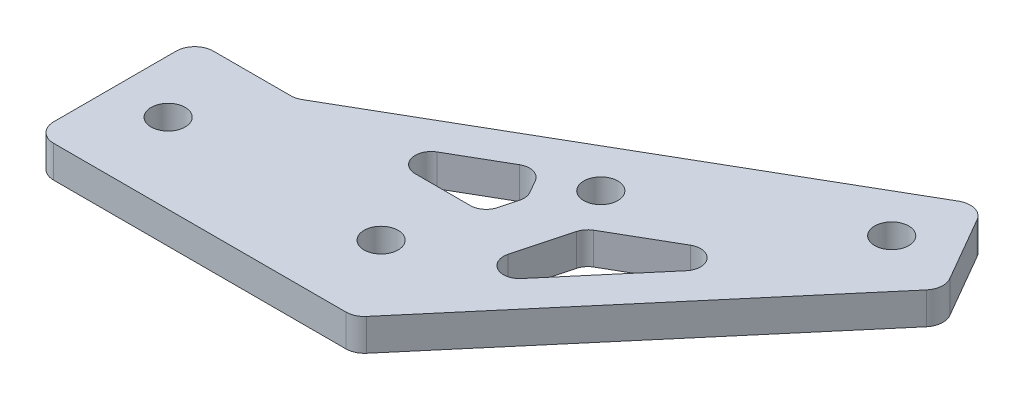
SolidWorks part; units mm, degrees
ref_plane "正面" through (0, 0, 0) normal (0, 0, 1) x (1, 0, 0)
ref_plane "平面" through (0, 0, 0) normal (0, 1, 0) x (1, 0, 0)
ref_plane "右側面" through (0, 0, 0) normal (1, 0, 0) x (0, 0, -1)
sketch "ｽｹｯﾁ1" plane through (0, 0, 0) normal (0, 1, 0) x (1, 0, 0)
  line L0 (164.476, -13.1178) -> (164.476, 1.8822) construction
  line L1 (164.476, 1.8822) -> (-55.524, 1.8822) construction
  line L3 (-55.524, -13.1178) -> (164.476, -13.1178) construction
  line L4 (26.6854, 10.5425) -> (31.6854, 1.8822) construction
  line L5 (31.6854, 1.8822) -> (334.7943, 176.8822) construction
  line L6 (334.7943, 176.8822) -> (329.7943, 185.5425) construction
  line L7 (329.7943, 185.5425) -> (26.6854, 10.5425) construction
  line L8 (164.476, -13.1178) -> (164.476, 1.8822) construction
  line L9 (164.476, 1.8822) -> (-55.524, 1.8822) construction
  line L11 (-55.524, -13.1178) -> (164.476, -13.1178) construction
  line L12 (26.6854, 10.5425) -> (31.6854, 1.8822) construction
  line L13 (31.6854, 1.8822) -> (334.7943, 176.8822) construction
  line L14 (334.7943, 176.8822) -> (329.7943, 185.5425) construction
  line L15 (329.7943, 185.5425) -> (26.6854, 10.5425) construction
  line L16 (29.47, 0) -> (419.1814, 225) construction
  line L17 (0, 0) -> (220, 0) construction
  line L18 (0, 0) -> (0, -15) construction
  line L19 (0, -15) -> (220, -15) construction
  line L20 (220, 0) -> (220, -15) construction
  line L21 (419.1814, 225) -> (414.1814, 233.6603) construction
  line L22 (414.1814, 233.6603) -> (24.47, 8.6603) construction
  line L23 (24.47, 8.6603) -> (29.47, 0) construction
  dimension "D1" = 15
  dimension "D2" = 220
  dimension "D3" = 29.47
  dimension "D4" = 30
  dimension "D5" = 450
  dimension "D6" = 10
sketch "ｽｹｯﾁ2" plane through (0, 0, 0) normal (0, 1, 0) x (1, 0, 0)
  line L0 (29.47, 0) -> (419.1814, 225) construction
  line L1 (24.47, 8.6603) -> (29.47, 0) construction
  line L2 (414.1814, 233.6603) -> (24.47, 8.6603) construction
  line L3 (220, 0) -> (220, -15) construction
  line L4 (0, -15) -> (220, -15) construction
  line L6 (0, 0) -> (220, 0) construction
  line L7 (29.47, 0) -> (419.1814, 225) construction
  line L8 (24.47, 8.6603) -> (29.47, 0) construction
  line L9 (414.1814, 233.6603) -> (24.47, 8.6603) construction
  line L10 (220, 0) -> (220, -15) construction
  line L11 (0, -15) -> (220, -15) construction
  line L13 (0, 0) -> (220, 0) construction
  line L14 (26.97, 4.3301) -> (48.6206, 16.8301) construction
  line L15 (0, -7.5) -> (25, -7.5) construction
  line L16 (24.47, 8.6603) -> (9.47, 0)
  line L18 (24.47, 8.6603) -> (50.4508, 23.6603)
  line L19 (50.4508, 23.6603) -> (55.4508, 15)
  line L20 (55.4508, 15) -> (30, -15)
  line L21 (30, -15) -> (0, -15)
  line L22 (0, -15) -> (0, 0)
  line L23 (0, 0) -> (9.47, 0)
  circle A0 centre (48.6206, 16.8301) radius 1.6
  circle A1 centre (25, -7.5) radius 1.6
  circle A2 centre (31.3001, 6.8301) radius 1.6
  circle A3 centre (5, -7.5) radius 1.6
  point P24 (0, -7.5)
  dimension "D3" = 3.2
  dimension "D4" = 3.2
  dimension "D5" = 3.2
  dimension "D6" = 3.2
  dimension "D1" = 25
  dimension "D2" = 25
  dimension "D7" = 5
  dimension "D8" = 5
  dimension "D9" = 5
  dimension "D10" = 5
extrude "ﾎﾞｽ - 押し出し1" add sketch "ｽｹｯﾁ2" along normal mid plane 3
sketch "ｽｹｯﾁ3" plane through (0, 1.5, 0) normal (0, 1, 0) x (1, 0, 0)
  line L0 (0, -15) -> (220, -15) construction
  line L1 (0, 0) -> (220, 0) construction
  line L2 (414.1814, 233.6603) -> (24.47, 8.6603) construction
  line L3 (24.47, 8.6603) -> (29.47, 0) construction
  line L4 (29.47, 0) -> (419.1814, 225) construction
  line L5 (0, -15) -> (220, -15)
  line L6 (0, 0) -> (220, 0)
  line L7 (414.1814, 233.6603) -> (24.47, 8.6603)
  line L8 (24.47, 8.6603) -> (29.47, 0)
  line L9 (29.47, 0) -> (419.1814, 225)
  line L10 (48.9867, 18.1962) -> (12.3252, -2.9704)
  line L11 (12.3252, -2.9704) -> (7.2558, -11)
  line L12 (7.2558, -11) -> (28.1479, -11)
  line L13 (28.1479, -11) -> (50.5782, 15.4396)
  line L14 (50.5782, 15.4396) -> (48.9867, 18.1962)
  line L15 (50.4508, 23.6603) -> (9.47, 0)
  line L16 (9.47, 0) -> (0, 0)
  line L17 (0, -15) -> (30, -15)
  line L18 (30, -15) -> (55.4508, 15)
  line L19 (55.4508, 15) -> (50.4508, 23.6603)
  line L20 (50.4508, 23.6603) -> (9.47, 0)
  line L22 (0, -15) -> (30, -15)
  line L23 (30, -15) -> (55.4508, 15)
  line L24 (55.4508, 15) -> (50.4508, 23.6603)
  line L25 (27.879, 2.7557) -> (27.1406, 0)
  line L26 (34.0628, 2.6517) -> (33.3523, 0)
  line L27 (0, -10.2338) -> (25, -7.5) construction
  line L28 (52.9508, 19.3301) -> (31.3001, 6.8301) construction
  line L29 (15.8097, 3.6603) -> (40.2703, -2.8939) construction
  line L30 (34.0628, 2.6517) -> (31.4468, -7.1115)
  line L37 (9.47, 0) -> (0, -15) construction
  line L38 (9.47, 0) -> (0, 0)
  line L39 (0, 0) -> (0, -15)
  line L40 (0, 0) -> (0, -15)
  dimension "D3" = 15
  dimension "D4" = 6
  dimension "D5" = 3.75
  dimension "D1" = 0
  dimension "D2" = 4
extrude "ｶｯﾄ - 押し出し1" cut sketch "ｽｹｯﾁ3" against normal blind 3 contours L25 L8 L10 L6 | L9 L26 L6 L13 | L6 L30 L13
fillet "ﾌｨﾚｯﾄ1" radius 1 7 edges at (45.1695, 0, -9.0641) (17.47, 0, 0) (26.47, 0, -5.1962) (27.879, 0, -2.7557) (27.1406, 0, 0) (31.4468, 0, 7.1115) (34.0628, 0, -2.6517)
fillet "ﾌｨﾚｯﾄ2" radius 1.75 6 edges at (50.4508, 0, -23.6603) (55.4508, 0, -15) (30, 0, 15) (9.47, 0, 0) (0, 0, 0) (0, 0, 15)
sketch "ｽｹｯﾁ4" plane through (0, -1.5, 0) normal (0, -1, 0) x (1, 0, 0)
  line L0 (50.4508, -23.6603) -> (55.4508, -15) construction
  line L1 (24.47, -8.6603) -> (50.4508, -23.6603) construction
  line L2 (24.47, -8.6603) -> (29.47, 0) construction
  line L3 (29.47, 0) -> (419.1814, -225) construction
  line L4 (55.4508, -15) -> (30, 15) construction
  line L5 (0, 0) -> (220, 0) construction
  line L6 (30, 15) -> (0, 15) construction
  line L7 (0, 15) -> (0, 0) construction
  line L8 (50.4508, -23.6603) -> (55.4508, -15)
  line L9 (24.47, -8.6603) -> (50.4508, -23.6603)
  line L10 (24.47, -8.6603) -> (29.47, 0)
  line L11 (29.47, 0) -> (419.1814, -225)
  line L12 (55.4508, -15) -> (30, 15)
  line L13 (0, 0) -> (220, 0)
  line L14 (30, 15) -> (0, 15)
  line L15 (0, 15) -> (0, 0)
  circle A0 centre (29.47, 0) radius 1
  dimension "D1" = 2
other "面の移動1" face at (33.2775, 0, 0.279) face at (33.2825, 0, 3.6083) face at (37.8848, 0, -0.4773) face at (41.1286, 0, -5.692) face at (37.3003, 0, -4.5208) face at (34.1584, 0, -2.5783) face at (20.5941, 0, -0.8371) face at (23.7877, 0, 0) face at (26.9192, 0, -0.2886) face at (27.5555, 0, -1.5484) face at (27.7596, 0, -2.74) face at (27.321, 0, -3.7223) face at (26.3249, 0, -4.6546) face at (23.153, 0, -3.2811) parameters "D1"=0.5
